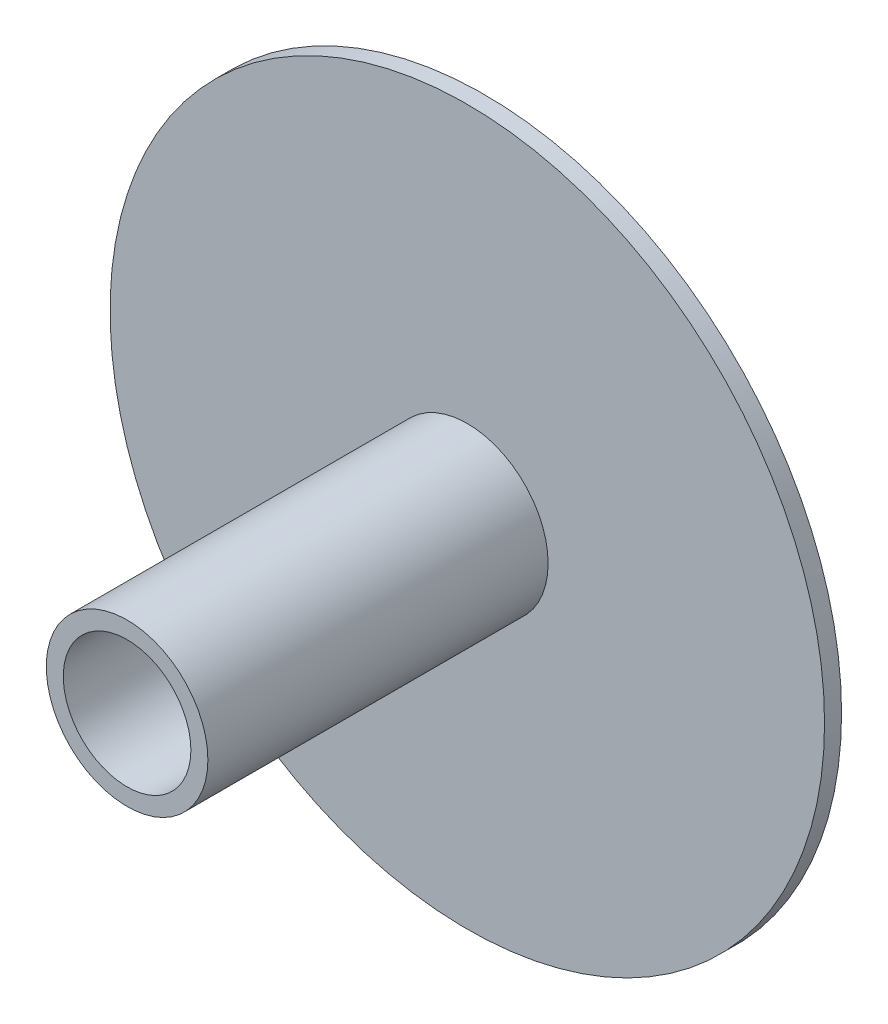
SolidWorks part; units mm, degrees
ref_plane "Front" through (0, 0, 0) normal (0, 0, 1) x (1, 0, 0)
ref_plane "Top" through (0, 0, 0) normal (0, 1, 0) x (1, 0, 0)
ref_plane "Right" through (0, 0, 0) normal (1, 0, 0) x (0, 0, -1)
sketch "Sketch1" plane through (0, 0, 0) normal (0, 0, 1) x (1, 0, 0)
  circle A0 centre (0, 0) radius 20 construction
  circle A1 centre (0, 0) radius 21
  dimension "D1" = 40
  dimension "D2" = 1
extrude "Boss-Extrude1" add sketch "Sketch1" along normal blind 1 contours A1
sketch "Sketch2" plane through (0, 0, 1) normal (0, 0, 1) x (1, 0, 0)
  circle A0 centre (0, 0) radius 3.75 construction
  circle A1 centre (0, 0) radius 4.75
  dimension "D2" = 1
  dimension "D1" = 7.5
extrude "Boss-Extrude2" add sketch "Sketch2" along normal blind 20
sketch "Sketch3" plane through (0, 0, 21) normal (0, 0, 1) x (1, 0, 0)
  circle A0 centre (0, 0) radius 3.75
  dimension "D1" = 7.5
extrude "Cut-Extrude1" cut sketch "Sketch3" against normal through all both and the other way through all contours A0
equation "\"D1@Sketch1\"=\"Cavity_Diameter\""
equation "\"Wall_Thickness\"= 1"
equation "\"Cavity_Diameter\"=40"
equation "\"D2@Sketch1\"=\"Wall_Thickness\""
equation "\"D1@Boss-Extrude1\"=\"Wall_Thickness\""
equation "\"Outlet_Diameter\" = 7.5"
equation "\"D1@Sketch2\"=\"Outlet_Diameter\""
equation "\"Outlet_Length\"= 20"
equation "\"D1@Boss-Extrude2\"=\"Outlet_Length\""
equation "\"D1@Sketch3\"=\"Outlet_Diameter\""
